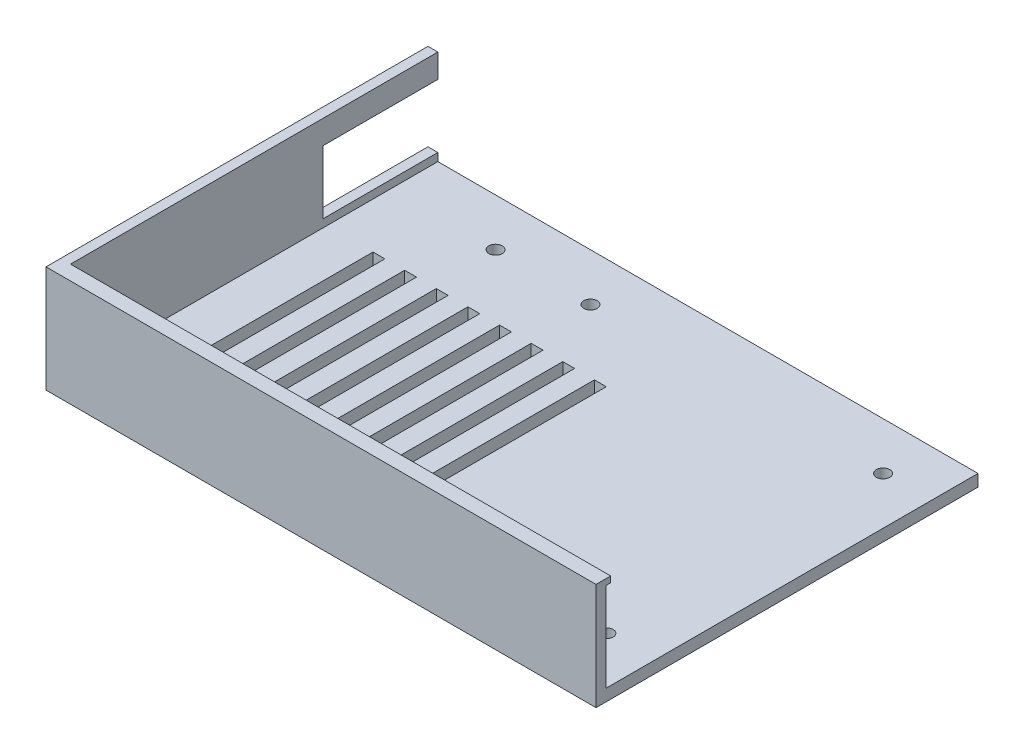
SolidWorks part; units mm, degrees
ref_plane "Front Plane" through (0, 0, 0) normal (0, 0, 1) x (1, 0, 0)
ref_plane "Top Plane" through (0, 0, 0) normal (0, 1, 0) x (1, 0, 0)
ref_plane "Right Plane" through (0, 0, 0) normal (1, 0, 0) x (0, 0, -1)
sketch "Sketch1" plane through (0, 0, 0) normal (0, 1, 0) x (1, 0, 0)
  line L1 (-139.1, -96.6) -> (139.1, -96.6)
  line L2 (-139.1, -96.6) -> (-139.1, 96.6)
  line L3 (-139.1, 96.6) -> (139.1, 96.6)
  line L4 (139.1, -96.6) -> (139.1, 96.6)
  line L5 (-139.1, -96.6) -> (139.1, 96.6) construction
  line L6 (-139.1, 96.6) -> (139.1, -96.6) construction
  point P0 (0, 0)
  dimension "D1" = 278.2
  dimension "D2" = 193.2
extrude "Shell Block" add sketch "Sketch1" along normal blind 27
ref_plane "Shell Front" through (0, 27, 0) normal (0, 1, 0) x (1, 0, 0)
sketch "Sketch2" plane through (0, 27, 0) normal (0, 1, 0) x (1, 0, 0)
  line L1 (-136.6, -92.9) -> (136.6, -92.9)
  line L2 (-136.6, -92.9) -> (-136.6, 92.9)
  line L3 (-136.6, 92.9) -> (136.6, 92.9)
  line L4 (136.6, -92.9) -> (136.6, 92.9)
  line L5 (-136.6, -92.9) -> (136.6, 92.9) construction
  line L6 (-136.6, 92.9) -> (136.6, -92.9) construction
  point P0 (0, 0)
  dimension "D1" = 273.2
  dimension "D2" = 185.8
extrude "Front Opening" cut sketch "Sketch2" against normal blind 1.5
ref_plane "Under Lip" through (0, 25.5, 0) normal (0, 1, 0) x (1, 0, 0)
sketch "Sketch3" plane through (0, 25.5, 0) normal (0, 1, 0) x (1, 0, 0)
  line L1 (-136.6, -94.1) -> (136.6, -94.1)
  line L2 (-136.6, -94.1) -> (-136.6, 94.1)
  line L3 (-136.6, 94.1) -> (136.6, 94.1)
  line L4 (136.6, -94.1) -> (136.6, 94.1)
  line L5 (-136.6, -94.1) -> (136.6, 94.1) construction
  line L6 (-136.6, 94.1) -> (136.6, -94.1) construction
  point P0 (0, 0)
  dimension "D1" = 273.2
  dimension "D2" = 188.2
extrude "Display Pocket" cut sketch "Sketch3" against normal blind 22.5
ref_plane "Back Inner" through (0, 3, 0) normal (0, 1, 0) x (1, 0, 0)
sketch "Sketch4" plane through (0, 3, 0) normal (0, 1, 0) x (1, 0, 0)
  line L1 (-69, 28) -> (-66, 28)
  line L2 (-69, 28) -> (-69, 84)
  line L3 (-69, 84) -> (-66, 84)
  line L4 (-66, 28) -> (-66, 84)
  line L6 (-69, -84) -> (-66, -84)
  line L7 (-69, -84) -> (-69, -28)
  line L8 (-69, -28) -> (-66, -28)
  line L9 (-66, -84) -> (-66, -28)
  line L11 (-77, 28) -> (-74, 28)
  line L12 (-77, 28) -> (-77, 84)
  line L13 (-77, 84) -> (-74, 84)
  line L14 (-74, 28) -> (-74, 84)
  line L16 (-77, -84) -> (-74, -84)
  line L17 (-77, -84) -> (-77, -28)
  line L18 (-77, -28) -> (-74, -28)
  line L19 (-74, -84) -> (-74, -28)
  line L21 (-85, 28) -> (-82, 28)
  line L22 (-85, 28) -> (-85, 84)
  line L23 (-85, 84) -> (-82, 84)
  line L24 (-82, 28) -> (-82, 84)
  line L26 (-85, -84) -> (-82, -84)
  line L27 (-85, -84) -> (-85, -28)
  line L28 (-85, -28) -> (-82, -28)
  line L29 (-82, -84) -> (-82, -28)
  line L31 (-93, 28) -> (-90, 28)
  line L32 (-93, 28) -> (-93, 84)
  line L33 (-93, 84) -> (-90, 84)
  line L34 (-90, 28) -> (-90, 84)
  line L36 (-93, -84) -> (-90, -84)
  line L37 (-93, -84) -> (-93, -28)
  line L38 (-93, -28) -> (-90, -28)
  line L39 (-90, -84) -> (-90, -28)
  line L41 (-101, 28) -> (-98, 28)
  line L42 (-101, 28) -> (-101, 84)
  line L43 (-101, 84) -> (-98, 84)
  line L44 (-98, 28) -> (-98, 84)
  line L46 (-101, -84) -> (-98, -84)
  line L47 (-101, -84) -> (-101, -28)
  line L48 (-101, -28) -> (-98, -28)
  line L49 (-98, -84) -> (-98, -28)
  line L51 (-109, 28) -> (-106, 28)
  line L52 (-109, 28) -> (-109, 84)
  line L53 (-109, 84) -> (-106, 84)
  line L54 (-106, 28) -> (-106, 84)
  line L56 (-109, -84) -> (-106, -84)
  line L57 (-109, -84) -> (-109, -28)
  line L58 (-109, -28) -> (-106, -28)
  line L59 (-106, -84) -> (-106, -28)
  line L61 (-117, 28) -> (-114, 28)
  line L62 (-117, 28) -> (-117, 84)
  line L63 (-117, 84) -> (-114, 84)
  line L64 (-114, 28) -> (-114, 84)
  line L66 (-117, -84) -> (-114, -84)
  line L67 (-117, -84) -> (-117, -28)
  line L68 (-117, -28) -> (-114, -28)
  line L69 (-114, -84) -> (-114, -28)
  line L71 (-125, 28) -> (-122, 28)
  line L72 (-125, 28) -> (-125, 84)
  line L73 (-125, 84) -> (-122, 84)
  line L74 (-122, 28) -> (-122, 84)
  line L76 (-125, -84) -> (-122, -84)
  line L77 (-125, -84) -> (-125, -28)
  line L78 (-125, -28) -> (-122, -28)
  line L79 (-122, -84) -> (-122, -28)
extrude "Vent Slots" cut sketch "Sketch4" against normal blind 4
sketch "Sketch5" plane through (0, 0, 0) normal (1, 0, 0) x (0, 0, -1)
  line L1 (-29, 5) -> (29, 5)
  line L2 (-29, 5) -> (-29, 21)
  line L3 (-29, 21) -> (29, 21)
  line L4 (29, 5) -> (29, 21)
extrude "Cable Exit (-X short side)" cut sketch "Sketch5" against normal blind 140.1
sketch "Sketch6" plane through (0, 3, 0) normal (0, 1, 0) x (1, 0, 0)
  circle A0 centre (-40, 18) radius 1.7
  circle A1 centre (-40, 88) radius 1.7
  circle A2 centre (40, 18) radius 1.7
  circle A3 centre (40, 88) radius 1.7
  circle A4 centre (-52, 40) radius 1.7
  circle A5 centre (-52, 66) radius 1.7
  circle A6 centre (52, 40) radius 1.7
  circle A7 centre (52, 66) radius 1.7
  circle A8 centre (-12, -82) radius 1.7
  circle A9 centre (12, -82) radius 1.7
  circle A10 centre (124, -12) radius 1.7
  circle A11 centre (124, 12) radius 1.7
  circle A12 centre (-12, -12) radius 1.7
  circle A13 centre (-12, 12) radius 1.7
  circle A14 centre (12, -12) radius 1.7
  circle A15 centre (12, 12) radius 1.7
  circle A16 centre (-110, 12) radius 1.7
  circle A17 centre (-110, -12) radius 1.7
  circle A18 centre (-86, 12) radius 1.7
  circle A19 centre (-86, -12) radius 1.7
extrude "Bolt Holes" cut sketch "Sketch6" against normal blind 4
sketch "Sketch7" plane through (0, 0, 0) normal (0, 1, 0) x (1, 0, 0)
  line L1 (200, -200) -> (0, -200)
  line L2 (200, -200) -> (200, 200)
  line L3 (200, 200) -> (0, 200)
  line L4 (0, -200) -> (0, 200)
extrude "Keep one half (X)" cut sketch "Sketch7" against normal through all and the other way through all
sketch "Sketch8" plane through (0, 0, 0) normal (0, 1, 0) x (1, 0, 0)
  line L1 (-200, 0) -> (200, 0)
  line L2 (-200, 0) -> (-200, 200)
  line L3 (-200, 200) -> (200, 200)
  line L4 (200, 0) -> (200, 200)
extrude "Keep one quarter (Z)" cut sketch "Sketch8" against normal through all and the other way through all
equation "\"DispL\"= 272.0"
equation "\"DispW\"= 187.0"
equation "\"DispT\"= 20.0"
equation "\"Clr\"= 0.6"
equation "\"Wall\"= 2.5"
equation "\"BackT\"= 3.0"
equation "\"CableRoom\"= 4.0"
equation "\"LipW\"= 1.2"
equation "\"LipT\"= 1.5"
equation "\"CableW\"= 58.0"
equation "\"CableH\"= 16.0"
equation "\"BoltD\"= 3.4"
equation "\"ShellL\"= \"DispL\" + 2 * \"Clr\" + 2 * \"Wall\""
equation "\"ShellW\"= \"DispW\" + 2 * \"Clr\" + 2 * \"Wall\""
equation "\"ShellH\"= \"BackT\" + \"DispT\" + \"CableRoom\""
equation "\"D1@Sketch1\" = \"ShellL\""
equation "\"D2@Sketch1\" = \"ShellW\""
equation "\"D1@Shell Block\" = \"ShellH\""
equation "\"D1@Shell Front\" = \"ShellH\""
equation "\"D1@Sketch2\" = \"DispL\" + 2 * \"Clr\""
equation "\"D2@Sketch2\" = \"DispW\" + 2 * \"Clr\" - 2 * \"LipW\""
equation "\"D1@Front Opening\" = \"LipT\""
equation "\"D1@Under Lip\" = \"ShellH\" - \"LipT\""
equation "\"D1@Sketch3\" = \"DispL\" + 2 * \"Clr\""
equation "\"D2@Sketch3\" = \"DispW\" + 2 * \"Clr\""
equation "\"D1@Display Pocket\" = \"ShellH\" - \"LipT\" - \"BackT\""
equation "\"D1@Back Inner\" = \"BackT\""
